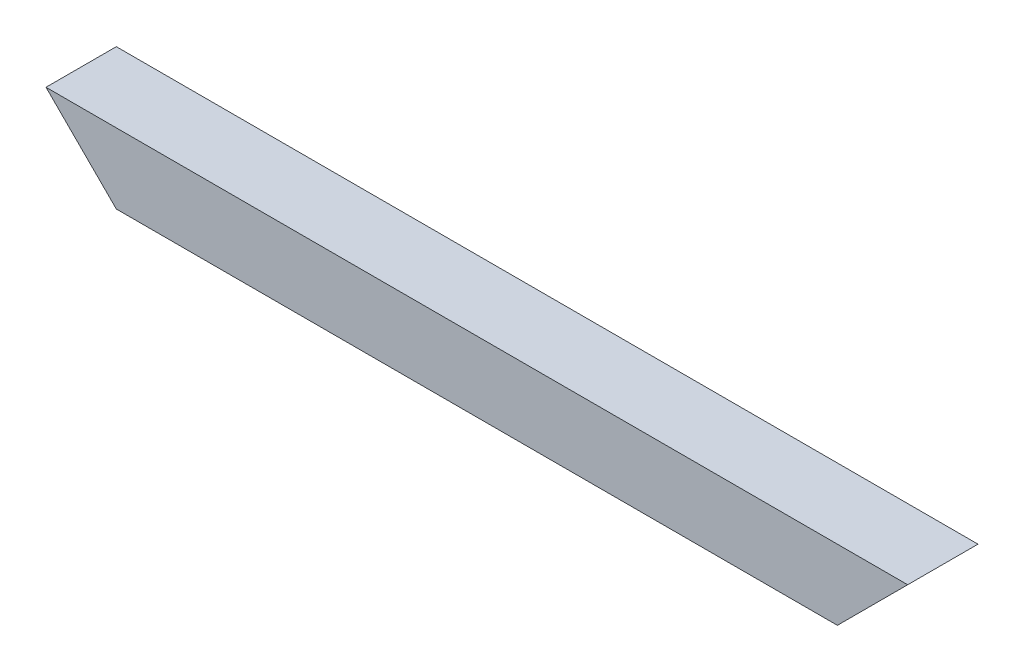
SolidWorks part; units mm, degrees
ref_plane "Front Plane" through (0, 0, 0) normal (0, 0, 1) x (1, 0, 0)
ref_plane "Top Plane" through (0, 0, 0) normal (0, 1, 0) x (1, 0, 0)
ref_plane "Right Plane" through (0, 0, 0) normal (1, 0, 0) x (0, 0, -1)
sketch "Sketch1" plane through (0, 0, 0) normal (1, 0, 0) x (0, 0, -1)
  line L1 (0, 0) -> (38.1, 0)
  line L2 (0, 0) -> (0, -38.1)
  line L3 (0, -38.1) -> (38.1, -38.1)
  line L4 (38.1, 0) -> (38.1, -38.1)
  dimension "D1" = 38.1
  dimension "D2" = 38.1
extrude "Boss-Extrude1" add sketch "Sketch1" along normal blind 466.9733
sketch "Sketch2" plane through (0, 0, 0) normal (0, 0, 1) x (1, 0, 0)
  line L0 (0, -38.1) -> (38.1, -38.1)
  line L1 (466.9733, -38.1) -> (0, -38.1) construction
  line L2 (38.1, -38.1) -> (0, 0)
  dimension "D1" = 38.1
extrude "Cut-Extrude1" cut sketch "Sketch2" against normal through all and the other way through all
sketch "Sketch3" plane through (0, 0, 0) normal (0, 0, 1) x (1, 0, 0)
  line L0 (466.9733, -38.1) -> (428.8733, -38.1)
  line L1 (466.9733, -38.1) -> (38.1, -38.1) construction
  line L2 (428.8733, -38.1) -> (466.9733, 0)
  dimension "D1" = 38.1
extrude "Cut-Extrude2" cut sketch "Sketch3" against normal through all and the other way through all flip side to cut
